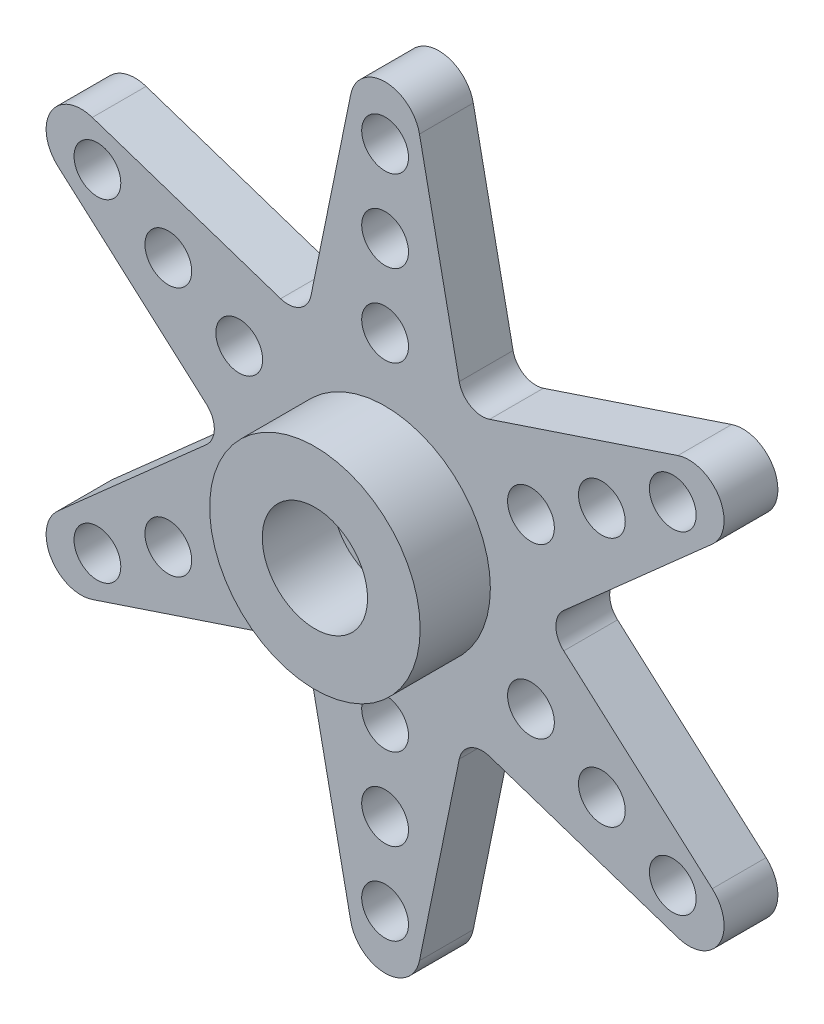
SolidWorks part; units mm, degrees
ref_plane "Front Plane" through (0, 0, 0) normal (0, 0, 1) x (1, 0, 0)
ref_plane "Top Plane" through (0, 0, 0) normal (0, 1, 0) x (1, 0, 0)
ref_plane "Right Plane" through (0, 0, 0) normal (1, 0, 0) x (0, 0, -1)
sketch "Sketch1" plane through (0, 0, 0) normal (0, 0, 1) x (1, 0, 0)
  line L0 (-3.1703, 6.9876) -> (-1.4696, 15.3007)
  line L1 (1.4696, 15.3007) -> (3.1703, 6.9876)
  line L2 (4.4663, 6.2393) -> (12.516, 8.923)
  line L3 (13.9855, 6.3776) -> (7.6366, 0.7482)
  line L4 (7.6366, -0.7482) -> (13.9855, -6.3776)
  line L5 (12.516, -8.923) -> (4.4663, -6.2393)
  line L6 (3.1703, -6.9876) -> (1.4696, -15.3007)
  line L7 (-1.4696, -15.3007) -> (-3.1703, -6.9876)
  line L8 (-4.4663, -6.2393) -> (-12.516, -8.923)
  line L9 (-13.9855, -6.3776) -> (-7.6366, -0.7482)
  line L10 (-7.6366, 0.7482) -> (-13.9855, 6.3776)
  line L11 (-12.516, 8.923) -> (-4.4663, 6.2393)
  arc A0 (-1.4696, 15.3007) -> (1.4696, 15.3007) centre (0, 15) cw
  arc A1 (3.1703, 6.9876) -> (4.4663, 6.2393) centre (4.15, 7.188) ccw
  arc A2 (12.516, 8.923) -> (13.9855, 6.3776) centre (12.9904, 7.5) cw
  arc A3 (7.6366, 0.7482) -> (7.6366, -0.7482) centre (8.3, 0) ccw
  arc A4 (13.9855, -6.3776) -> (12.516, -8.923) centre (12.9904, -7.5) cw
  arc A5 (4.4663, -6.2393) -> (3.1703, -6.9876) centre (4.15, -7.188) ccw
  arc A6 (1.4696, -15.3007) -> (-1.4696, -15.3007) centre (0, -15) cw
  arc A7 (-3.1703, -6.9876) -> (-4.4663, -6.2393) centre (-4.15, -7.188) ccw
  arc A8 (-12.516, -8.923) -> (-13.9855, -6.3776) centre (-12.9904, -7.5) cw
  arc A9 (-7.6366, -0.7482) -> (-7.6366, 0.7482) centre (-8.3, 0) ccw
  arc A10 (-13.9855, 6.3776) -> (-12.516, 8.923) centre (-12.9904, 7.5) cw
  arc A11 (-4.4663, 6.2393) -> (-3.1703, 6.9876) centre (-4.15, 7.188) ccw
  circle A12 centre (0, 14.2) radius 1
  circle A13 centre (0, 10.7) radius 1
  circle A14 centre (0, 7.2) radius 1
  circle A15 centre (6.2354, 3.6) radius 1
  circle A16 centre (9.2665, 5.35) radius 1
  circle A17 centre (12.2976, 7.1) radius 1
  circle A18 centre (6.2354, -3.6) radius 1
  circle A19 centre (9.2665, -5.35) radius 1
  circle A20 centre (12.2976, -7.1) radius 1
  circle A21 centre (0, -7.2) radius 1
  circle A22 centre (0, -10.7) radius 1
  circle A23 centre (0, -14.2) radius 1
  circle A24 centre (-6.2354, -3.6) radius 1
  circle A25 centre (-9.2665, -5.35) radius 1
  circle A26 centre (-12.2976, -7.1) radius 1
  circle A27 centre (-6.2354, 3.6) radius 1
  circle A28 centre (-9.2665, 5.35) radius 1
  circle A29 centre (-12.2976, 7.1) radius 1
  point P45 (0, 0)
  point P77 (0, 0)
  dimension "D3" = 2
  dimension "D7" = 1.5
  dimension "D8" = 1
  dimension "D2" = 15
  dimension "D4" = 7.2
  dimension "D5" = 3.5
  dimension "D6" = 3.5
  dimension "D9" = 8.3
  dimension "D1" = 6
  dimension "D10" = 6
extrude "Boss-Extrude1" add sketch "Sketch1" along normal blind 2.3
sketch "Sketch2" plane through (0, 0, 2.3) normal (0, 0, 1) x (1, 0, 0)
  circle A0 centre (0, 0) radius 1.5
  dimension "D1" = 3
extrude "Cut-Extrude1" cut sketch "Sketch2" against normal up to next
sketch "Sketch3" plane through (0, 0, 2.3) normal (0, 0, 1) x (1, 0, 0)
  circle A0 centre (0, 0) radius 4.5
  circle A1 centre (0, 0) radius 2.25
  dimension "D1" = 9
  dimension "D2" = 4.5
extrude "Boss-Extrude2" add sketch "Sketch3" along normal blind 3
